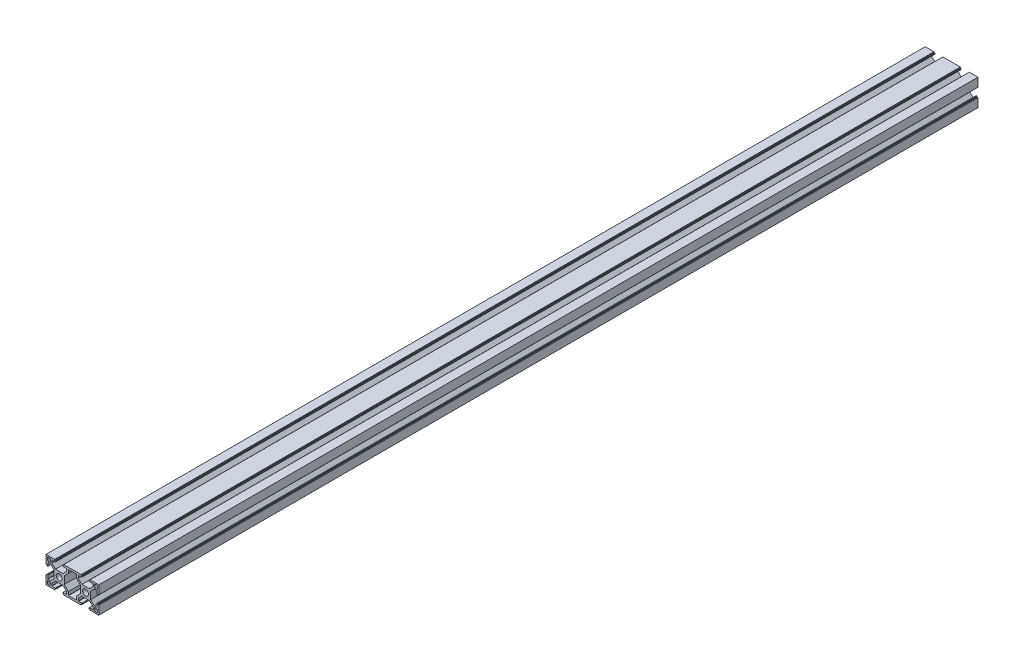
SolidWorks part; units mm, degrees
ref_plane "前视基准面" through (0, 0, 0) normal (0, 0, 1) x (1, 0, 0)
ref_plane "上视基准面" through (0, 0, 0) normal (0, 1, 0) x (1, 0, 0)
ref_plane "右视基准面" through (0, 0, 0) normal (1, 0, 0) x (0, 0, -1)
sketch "草图1" plane through (0, 0, 0) normal (0, 0, 1) x (1, 0, 0)
  line L0 (-29.6103, -11.7894) -> (-29.6103, -13.5394)
  line L1 (-30.6103, -14.5394) -> (-32.3603, -14.5394)
  line L2 (-33.3603, -13.5394) -> (-33.3603, -11.7894)
  line L3 (-32.3603, -10.7894) -> (-30.6103, -10.7894)
  line L4 (-30.6103, 8.7106) -> (-32.3603, 8.7106)
  line L5 (-33.3603, 9.7106) -> (-33.3603, 11.4606)
  line L6 (-32.3603, 12.4606) -> (-30.6103, 12.4606)
  line L7 (-29.6103, 11.4606) -> (-29.6103, 9.7106)
  line L8 (-34.8603, 11.4606) -> (-34.8603, 4.0606)
  line L9 (-34.8603, 4.0606) -> (-34.0603, 4.0606)
  line L10 (-33.8603, 3.8606) -> (-33.8603, 3.0606)
  line L11 (-33.8603, 3.0606) -> (-32.9603, 3.0606)
  line L12 (-32.6603, 3.3606) -> (-32.6603, 6.9106)
  line L13 (-32.3603, 7.2106) -> (-29.666, 7.2106)
  line L14 (-29.666, 7.2106) -> (-25.6603, 3.205)
  line L15 (-25.6603, 3.205) -> (-25.6603, -5.2838)
  line L16 (-25.6603, -5.2838) -> (-29.666, -9.2894)
  line L17 (-29.666, -9.2894) -> (-32.3603, -9.2894)
  line L18 (-32.6603, -8.9894) -> (-32.6603, -5.4394)
  line L19 (-32.9603, -5.1394) -> (-33.8603, -5.1394)
  line L20 (-33.8603, -5.1394) -> (-33.8603, -5.9394)
  line L21 (-34.0603, -6.1394) -> (-34.8603, -6.1394)
  line L22 (-34.8603, -6.1394) -> (-34.8603, -13.5394)
  line L23 (-32.3603, -16.0394) -> (-24.9603, -16.0394)
  line L24 (-24.9603, -16.0394) -> (-24.9603, -15.2394)
  line L25 (-24.7603, -15.0394) -> (-23.9603, -15.0394)
  line L26 (-23.9603, -15.0394) -> (-23.9603, -14.1394)
  line L27 (-24.2603, -13.8394) -> (-27.8103, -13.8394)
  line L28 (-28.1103, -13.5394) -> (-28.1103, -10.845)
  line L29 (-28.1103, -10.845) -> (-24.1047, -6.8394)
  line L30 (-24.1047, -6.8394) -> (-15.616, -6.8394)
  line L31 (-15.616, -6.8394) -> (-11.6103, -10.845)
  line L32 (-11.6103, -10.845) -> (-11.6103, -13.5394)
  line L33 (-11.9103, -13.8394) -> (-15.4603, -13.8394)
  line L34 (-15.7603, -14.1394) -> (-15.7603, -15.0394)
  line L35 (-15.7603, -15.0394) -> (-14.9603, -15.0394)
  line L36 (-14.7603, -15.2394) -> (-14.7603, -16.0394)
  line L37 (-14.7603, -16.0394) -> (-7.3603, -16.0394)
  line L39 (-14.0603, -5.2838) -> (-14.0603, 3.205)
  line L41 (-7.3603, 13.9606) -> (-14.7603, 13.9606)
  line L42 (-14.7603, 13.9606) -> (-14.7603, 13.1606)
  line L43 (-14.9603, 12.9606) -> (-15.7603, 12.9606)
  line L44 (-15.7603, 12.9606) -> (-15.7603, 12.0606)
  line L45 (-15.4603, 11.7606) -> (-11.9103, 11.7606)
  line L46 (-11.6103, 11.4606) -> (-11.6103, 8.7662)
  line L47 (-11.6103, 8.7662) -> (-15.616, 4.7606)
  line L48 (-15.616, 4.7606) -> (-24.1047, 4.7606)
  line L49 (-24.1047, 4.7606) -> (-28.1103, 8.7662)
  line L50 (-28.1103, 8.7662) -> (-28.1103, 11.4606)
  line L51 (-27.8103, 11.7606) -> (-24.2603, 11.7606)
  line L52 (-23.9603, 12.0606) -> (-23.9603, 12.9606)
  line L53 (-23.9603, 12.9606) -> (-24.7603, 12.9606)
  line L54 (-24.9603, 13.1606) -> (-24.9603, 13.9606)
  line L55 (-24.9603, 13.9606) -> (-32.3603, 13.9606)
  line L56 (-32.3603, 13.9606) -> (-34.8603, 13.9606)
  line L57 (-34.8603, 13.9606) -> (-34.8603, 11.4606)
  line L58 (-7.3603, 13.9606) -> (-4.8603, 13.9606)
  line L59 (-32.3603, -16.0394) -> (-34.8603, -16.0394)
  line L60 (-34.8603, -16.0394) -> (-34.8603, -13.5394)
  line L61 (-7.3603, -16.0394) -> (-4.8603, -16.0394)
  line L62 (19.8897, 9.7106) -> (19.8897, 11.4606)
  line L63 (20.8897, 12.4606) -> (22.6397, 12.4606)
  line L64 (23.6397, 11.4606) -> (23.6397, 9.7106)
  line L65 (22.6397, 8.7106) -> (20.8897, 8.7106)
  line L66 (20.8897, -10.7894) -> (22.6397, -10.7894)
  line L67 (23.6397, -11.7894) -> (23.6397, -13.5394)
  line L68 (22.6397, -14.5394) -> (20.8897, -14.5394)
  line L69 (19.8897, -13.5394) -> (19.8897, -11.7894)
  line L70 (-4.8603, -16.0394) -> (-2.3603, -16.0394)
  line L71 (-2.3603, -16.0394) -> (5.0397, -16.0394)
  line L72 (5.0397, -16.0394) -> (5.0397, -15.2394)
  line L73 (5.2397, -15.0394) -> (6.0397, -15.0394)
  line L74 (6.0397, -15.0394) -> (6.0397, -14.1394)
  line L75 (5.7397, -13.8394) -> (2.1897, -13.8394)
  line L76 (1.8897, -13.5394) -> (1.8897, -10.845)
  line L77 (1.8897, -10.845) -> (5.8953, -6.8394)
  line L78 (5.8953, -6.8394) -> (14.384, -6.8394)
  line L79 (14.384, -6.8394) -> (18.3897, -10.845)
  line L80 (18.3897, -10.845) -> (18.3897, -13.5394)
  line L81 (18.0897, -13.8394) -> (14.5397, -13.8394)
  line L82 (14.2397, -14.1394) -> (14.2397, -15.0394)
  line L83 (14.2397, -15.0394) -> (15.0397, -15.0394)
  line L84 (15.2397, -15.2394) -> (15.2397, -16.0394)
  line L85 (15.2397, -16.0394) -> (22.6397, -16.0394)
  line L86 (22.6397, -16.0394) -> (25.1397, -16.0394)
  line L87 (25.1397, -16.0394) -> (25.1397, -13.5394)
  line L88 (25.1397, -13.5394) -> (25.1397, -6.1394)
  line L89 (25.1397, -6.1394) -> (24.3397, -6.1394)
  line L90 (24.1397, -5.9394) -> (24.1397, -5.1394)
  line L91 (24.1397, -5.1394) -> (23.2397, -5.1394)
  line L92 (22.9397, -5.4394) -> (22.9397, -8.9894)
  line L93 (22.6397, -9.2894) -> (19.9453, -9.2894)
  line L94 (19.9453, -9.2894) -> (15.9397, -5.2838)
  line L95 (15.9397, -5.2838) -> (15.9397, 3.205)
  line L96 (15.9397, 3.205) -> (19.9453, 7.2106)
  line L97 (19.9453, 7.2106) -> (22.6397, 7.2106)
  line L98 (22.9397, 6.9106) -> (22.9397, 3.3606)
  line L99 (23.2397, 3.0606) -> (24.1397, 3.0606)
  line L100 (24.1397, 3.0606) -> (24.1397, 3.8606)
  line L101 (24.3397, 4.0606) -> (25.1397, 4.0606)
  line L102 (25.1397, 4.0606) -> (25.1397, 11.4606)
  line L103 (25.1397, 11.4606) -> (25.1397, 13.9606)
  line L104 (25.1397, 13.9606) -> (22.6397, 13.9606)
  line L105 (22.6397, 13.9606) -> (15.2397, 13.9606)
  line L106 (15.2397, 13.9606) -> (15.2397, 13.1606)
  line L107 (15.0397, 12.9606) -> (14.2397, 12.9606)
  line L108 (14.2397, 12.9606) -> (14.2397, 12.0606)
  line L109 (14.5397, 11.7606) -> (18.0897, 11.7606)
  line L110 (18.3897, 11.4606) -> (18.3897, 8.7662)
  line L111 (18.3897, 8.7662) -> (14.384, 4.7606)
  line L112 (14.384, 4.7606) -> (5.8953, 4.7606)
  line L113 (5.8953, 4.7606) -> (1.8897, 8.7662)
  line L114 (1.8897, 8.7662) -> (1.8897, 11.4606)
  line L115 (2.1897, 11.7606) -> (5.7397, 11.7606)
  line L116 (6.0397, 12.0606) -> (6.0397, 12.9606)
  line L117 (6.0397, 12.9606) -> (5.2397, 12.9606)
  line L118 (5.0397, 13.1606) -> (5.0397, 13.9606)
  line L119 (5.0397, 13.9606) -> (-2.3603, 13.9606)
  line L120 (-2.3603, 13.9606) -> (-4.8603, 13.9606)
  line L121 (-14.0603, 3.205) -> (-9.4103, 7.855)
  line L122 (-9.4103, 7.855) -> (-9.4103, 11.4606)
  line L123 (-9.1103, 11.7606) -> (-0.6103, 11.7606)
  line L124 (-0.3103, 11.4606) -> (-0.3103, 7.855)
  line L125 (-0.3103, 7.855) -> (4.3397, 3.205)
  line L126 (4.3397, 3.205) -> (4.3397, -5.2838)
  line L127 (4.3397, -5.2838) -> (-0.3103, -9.9338)
  line L128 (-0.3103, -9.9338) -> (-0.3103, -13.5394)
  line L129 (-0.6103, -13.8394) -> (-9.1103, -13.8394)
  line L130 (-9.4103, -13.5394) -> (-9.4103, -9.9338)
  line L131 (-9.4103, -9.9338) -> (-14.0603, -5.2838)
  arc A0 (-30.6103, -14.5394) -> (-29.6103, -13.5394) centre (-30.6103, -13.5394) ccw
  arc A1 (-33.3603, -13.5394) -> (-32.3603, -14.5394) centre (-32.3603, -13.5394) ccw
  arc A2 (-32.3603, -10.7894) -> (-33.3603, -11.7894) centre (-32.3603, -11.7894) ccw
  arc A3 (-29.6103, -11.7894) -> (-30.6103, -10.7894) centre (-30.6103, -11.7894) ccw
  arc A4 (-33.3603, 9.7106) -> (-32.3603, 8.7106) centre (-32.3603, 9.7106) ccw
  arc A5 (-32.3603, 12.4606) -> (-33.3603, 11.4606) centre (-32.3603, 11.4606) ccw
  arc A6 (-29.6103, 11.4606) -> (-30.6103, 12.4606) centre (-30.6103, 11.4606) ccw
  arc A7 (-30.6103, 8.7106) -> (-29.6103, 9.7106) centre (-30.6103, 9.7106) ccw
  circle A8 centre (-19.8603, -1.0394) radius 3.4
  arc A9 (-33.8603, 3.8606) -> (-34.0603, 4.0606) centre (-34.0603, 3.8606) ccw
  arc A10 (-32.9603, 3.0606) -> (-32.6603, 3.3606) centre (-32.9603, 3.3606) ccw
  arc A11 (-32.3603, 7.2106) -> (-32.6603, 6.9106) centre (-32.3603, 6.9106) ccw
  arc A12 (-32.6603, -8.9894) -> (-32.3603, -9.2894) centre (-32.3603, -8.9894) ccw
  arc A13 (-32.6603, -5.4394) -> (-32.9603, -5.1394) centre (-32.9603, -5.4394) ccw
  arc A14 (-34.0603, -6.1394) -> (-33.8603, -5.9394) centre (-34.0603, -5.9394) ccw
  arc A15 (-24.7603, -15.0394) -> (-24.9603, -15.2394) centre (-24.7603, -15.2394) ccw
  arc A16 (-23.9603, -14.1394) -> (-24.2603, -13.8394) centre (-24.2603, -14.1394) ccw
  arc A17 (-28.1103, -13.5394) -> (-27.8103, -13.8394) centre (-27.8103, -13.5394) ccw
  arc A18 (-11.9103, -13.8394) -> (-11.6103, -13.5394) centre (-11.9103, -13.5394) ccw
  arc A19 (-15.4603, -13.8394) -> (-15.7603, -14.1394) centre (-15.4603, -14.1394) ccw
  arc A20 (-14.7603, -15.2394) -> (-14.9603, -15.0394) centre (-14.9603, -15.2394) ccw
  arc A21 (-14.9603, 12.9606) -> (-14.7603, 13.1606) centre (-14.9603, 13.1606) ccw
  arc A22 (-15.7603, 12.0606) -> (-15.4603, 11.7606) centre (-15.4603, 12.0606) ccw
  arc A23 (-11.6103, 11.4606) -> (-11.9103, 11.7606) centre (-11.9103, 11.4606) ccw
  arc A24 (-27.8103, 11.7606) -> (-28.1103, 11.4606) centre (-27.8103, 11.4606) ccw
  arc A25 (-24.2603, 11.7606) -> (-23.9603, 12.0606) centre (-24.2603, 12.0606) ccw
  arc A26 (-24.9603, 13.1606) -> (-24.7603, 12.9606) centre (-24.7603, 13.1606) ccw
  arc A27 (20.8897, 12.4606) -> (19.8897, 11.4606) centre (20.8897, 11.4606) ccw
  arc A28 (23.6397, 11.4606) -> (22.6397, 12.4606) centre (22.6397, 11.4606) ccw
  arc A29 (22.6397, 8.7106) -> (23.6397, 9.7106) centre (22.6397, 9.7106) ccw
  arc A30 (19.8897, 9.7106) -> (20.8897, 8.7106) centre (20.8897, 9.7106) ccw
  arc A31 (23.6397, -11.7894) -> (22.6397, -10.7894) centre (22.6397, -11.7894) ccw
  arc A32 (22.6397, -14.5394) -> (23.6397, -13.5394) centre (22.6397, -13.5394) ccw
  arc A33 (19.8897, -13.5394) -> (20.8897, -14.5394) centre (20.8897, -13.5394) ccw
  arc A34 (20.8897, -10.7894) -> (19.8897, -11.7894) centre (20.8897, -11.7894) ccw
  circle A35 centre (10.1397, -1.0394) radius 3.4
  arc A36 (5.2397, -15.0394) -> (5.0397, -15.2394) centre (5.2397, -15.2394) ccw
  arc A37 (6.0397, -14.1394) -> (5.7397, -13.8394) centre (5.7397, -14.1394) ccw
  arc A38 (1.8897, -13.5394) -> (2.1897, -13.8394) centre (2.1897, -13.5394) ccw
  arc A39 (18.0897, -13.8394) -> (18.3897, -13.5394) centre (18.0897, -13.5394) ccw
  arc A40 (14.5397, -13.8394) -> (14.2397, -14.1394) centre (14.5397, -14.1394) ccw
  arc A41 (15.2397, -15.2394) -> (15.0397, -15.0394) centre (15.0397, -15.2394) ccw
  arc A42 (24.1397, -5.9394) -> (24.3397, -6.1394) centre (24.3397, -5.9394) ccw
  arc A43 (23.2397, -5.1394) -> (22.9397, -5.4394) centre (23.2397, -5.4394) ccw
  arc A44 (22.6397, -9.2894) -> (22.9397, -8.9894) centre (22.6397, -8.9894) ccw
  arc A45 (22.9397, 6.9106) -> (22.6397, 7.2106) centre (22.6397, 6.9106) ccw
  arc A46 (22.9397, 3.3606) -> (23.2397, 3.0606) centre (23.2397, 3.3606) ccw
  arc A47 (24.3397, 4.0606) -> (24.1397, 3.8606) centre (24.3397, 3.8606) ccw
  arc A48 (15.0397, 12.9606) -> (15.2397, 13.1606) centre (15.0397, 13.1606) ccw
  arc A49 (14.2397, 12.0606) -> (14.5397, 11.7606) centre (14.5397, 12.0606) ccw
  arc A50 (18.3897, 11.4606) -> (18.0897, 11.7606) centre (18.0897, 11.4606) ccw
  arc A51 (2.1897, 11.7606) -> (1.8897, 11.4606) centre (2.1897, 11.4606) ccw
  arc A52 (5.7397, 11.7606) -> (6.0397, 12.0606) centre (5.7397, 12.0606) ccw
  arc A53 (5.0397, 13.1606) -> (5.2397, 12.9606) centre (5.2397, 13.1606) ccw
  arc A54 (-9.1103, 11.7606) -> (-9.4103, 11.4606) centre (-9.1103, 11.4606) ccw
  arc A55 (-0.3103, 11.4606) -> (-0.6103, 11.7606) centre (-0.6103, 11.4606) ccw
  arc A56 (-0.6103, -13.8394) -> (-0.3103, -13.5394) centre (-0.6103, -13.5394) ccw
  arc A57 (-9.4103, -13.5394) -> (-9.1103, -13.8394) centre (-9.1103, -13.5394) ccw
extrude "凸台-拉伸1" add sketch "草图1" along normal blind 1000
